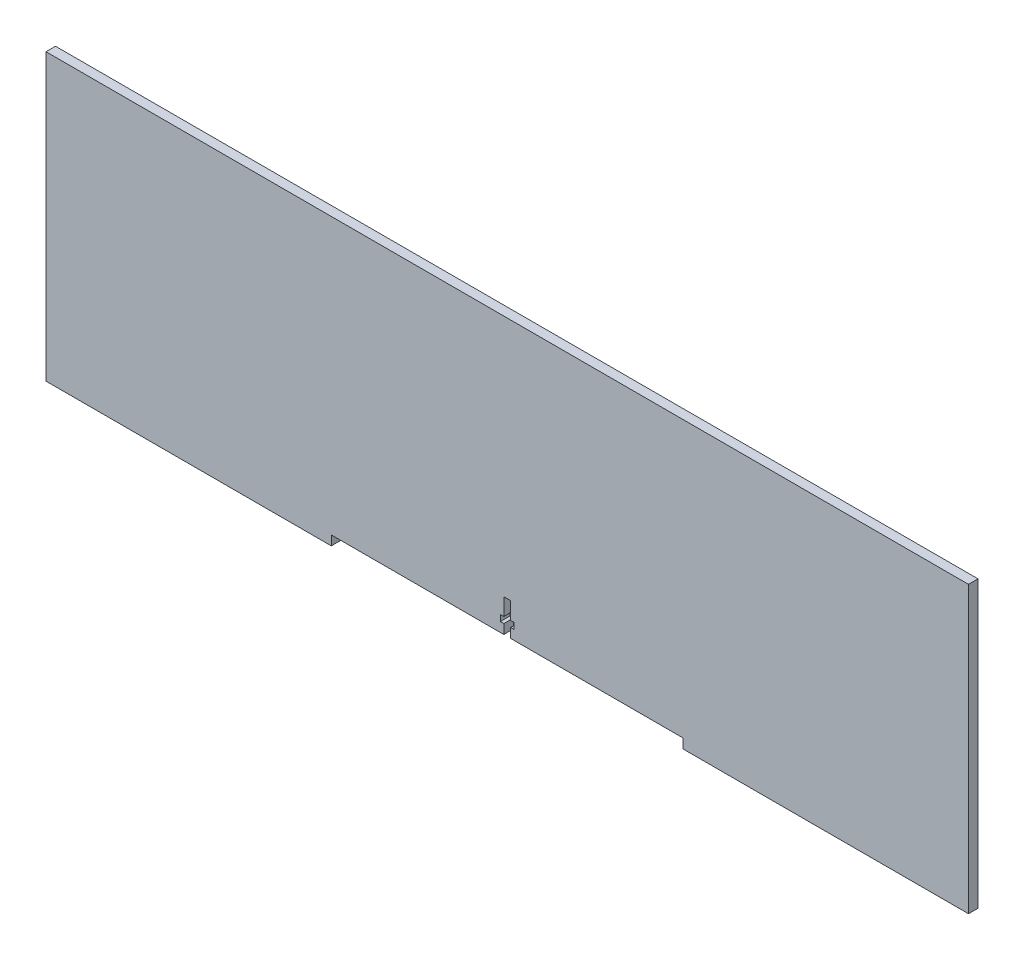
SolidWorks part; units mm, degrees
ref_plane "Alzado" through (0, 0, 0) normal (0, 0, 1) x (1, 0, 0)
ref_plane "Planta" through (0, 0, 0) normal (0, 1, 0) x (1, 0, 0)
ref_plane "Vista lateral" through (0, 0, 0) normal (1, 0, 0) x (0, 0, -1)
sketch "Croquis1" plane through (0, 0, 0) normal (0, 0, 1) x (1, 0, 0)
  line L0 (820, 0) -> (820, -363.7923) construction
  line L1 (0, 0) -> (185, 0)
  line L2 (0, 0) -> (0, 145)
  line L3 (0, 145) -> (1640, 145)
  line L4 (1640, 0) -> (1640, 145)
  line L5 (183.7346, 0) -> (185, 0)
  line L9 (485, -5) -> (185, -5)
  line L11 (670, 0) -> (670, -5)
  line L12 (670, -5) -> (970, -5)
  line L13 (970, 0) -> (970, -5)
  line L15 (1155, 0) -> (1155, -5)
  line L16 (1155, -5) -> (1455, -5)
  line L17 (1455, 0) -> (1455, -5)
  line L18 (185, 0) -> (185, -5)
  line L19 (485, 0) -> (481.1866, 0)
  line L20 (485, 0) -> (485, -5)
  line L21 (481.1866, 0) -> (670, 0)
  line L22 (970, 0) -> (1155, 0)
  line L23 (1455, 0) -> (1640, 0)
  point P15 (820, -5)
  dimension "D1" = 1640
  dimension "D2" = 145
  dimension "D3" = 5
  dimension "D4" = 185
  dimension "D5" = 300
  dimension "D6" = 300
  dimension "D7" = 5
  dimension "D8" = 185
extrude "Saliente-Extruir1" add sketch "Croquis1" along normal blind 5
sketch "Croquis2" plane through (0, 0, 5) normal (0, 0, 1) x (1, 0, 0)
  line L0 (1640, 72.5) -> (1561.7814, 72.5) construction
  line L1 (1640, 0) -> (1640, 145) construction
  line L2 (0, 145) -> (1640, 145) construction
  line L3 (1640, 126.25) -> (1635, 126.25)
  line L4 (1640, 126.25) -> (1640, 91.25)
  line L5 (1640, 91.25) -> (1635, 91.25)
  line L6 (1635, 126.25) -> (1635, 91.25)
  line L7 (1640, 53.75) -> (1635, 53.75)
  line L8 (1635, 18.75) -> (1635, 53.75)
  line L9 (1640, 18.75) -> (1635, 18.75)
  line L10 (1640, 18.75) -> (1640, 53.75)
  line L11 (820, 145) -> (820, 72.5) construction
  line L12 (0, 18.75) -> (0, 53.75)
  line L13 (0, 18.75) -> (5, 18.75)
  line L14 (5, 18.75) -> (5, 53.75)
  line L15 (0, 53.75) -> (5, 53.75)
  line L16 (0, 91.25) -> (5, 91.25)
  line L17 (5, 126.25) -> (5, 91.25)
  line L18 (0, 126.25) -> (5, 126.25)
  line L19 (0, 126.25) -> (0, 91.25)
  dimension "D1" = 35
  dimension "D2" = 18.75
  dimension "D3" = 5
extrude "Cortar-Extruir1" cut sketch "Croquis2" against normal blind 5 contours L7 L8 L9 L10 | L4 L3 L6 L5 | L16 L17 L18 L19 | L12 L15 L14 L13
sketch "Croquis3" plane through (0, 0, 5) normal (0, 0, 1) x (1, 0, 0)
  line L0 (577.5, 0) -> (577.5, 72.6456) construction
  line L1 (485, 0) -> (670, 0) construction
  line L2 (820, -5) -> (820, 72.6456) construction
  line L3 (670, -5) -> (970, -5) construction
  line L4 (579.3, 0) -> (575.7, 0)
  line L5 (575.7, 0) -> (575.7, 5)
  line L6 (575.7, 5) -> (573.9, 5)
  line L7 (573.9, 5) -> (573.9, 8.2)
  line L8 (573.9, 8.2) -> (575.7, 8.2)
  line L9 (575.7, 8.2) -> (575.7, 17.2)
  line L10 (575.7, 17.2) -> (579.3, 17.2)
  line L11 (579.3, 8.2) -> (579.3, 17.2)
  line L12 (581.1, 8.2) -> (579.3, 8.2)
  line L13 (581.1, 5) -> (581.1, 8.2)
  line L14 (579.3, 5) -> (581.1, 5)
  line L15 (579.3, 0) -> (579.3, 5)
  line L16 (1064.3, 8.2) -> (1064.3, 17.2)
  line L17 (1066.1, 8.2) -> (1064.3, 8.2)
  line L18 (1066.1, 5) -> (1066.1, 8.2)
  line L19 (1064.3, 5) -> (1066.1, 5)
  line L20 (1064.3, 0) -> (1064.3, 5)
  line L21 (1060.7, 0) -> (1064.3, 0)
  line L22 (1060.7, 0) -> (1060.7, 5)
  line L23 (1060.7, 5) -> (1058.9, 5)
  line L24 (1058.9, 5) -> (1058.9, 8.2)
  line L25 (1058.9, 8.2) -> (1060.7, 8.2)
  line L26 (1060.7, 8.2) -> (1060.7, 17.2)
  line L27 (1064.3, 17.2) -> (1060.7, 17.2)
  point P16 (577.5, 17.2)
  dimension "D1" = 1.8
  dimension "D2" = 5
  dimension "D3" = 1.8
  dimension "D4" = 3.2
  dimension "D5" = 1.8
  dimension "D6" = 9
extrude "Cortar-Extruir2" cut sketch "Croquis3" against normal blind 10 contours L10 L11 L12 L13 L14 L15 L4 L5 L6 L7 L8 L9 | L16 L27 L26 L25 L24 L23 L22 L21 L20 L19 L18 L17
sketch "Croquis4" plane through (0, 0, 5) normal (0, 0, 1) x (1, 0, 0)
  line L0 (335, -5) -> (335, 145)
  line L1 (485, -5) -> (185, -5) construction
  line L2 (0, 145) -> (1640, 145) construction
  line L3 (335, 145) -> (820, 145)
  line L4 (820, 145) -> (820, -5)
  line L5 (670, -5) -> (970, -5) construction
  line L6 (820, -5) -> (335, -5)
  line L7 (820, 145) -> (1680.9053, 145)
  line L8 (1680.9053, 145) -> (1680.9053, -135.2151)
  line L9 (1680.9053, -135.2151) -> (820, -135.2151)
  line L10 (820, -135.2151) -> (820, -5)
  line L11 (335, -5) -> (335, -117.5316)
  line L12 (335, -117.5316) -> (-54.1262, -117.5316)
  line L13 (-54.1262, -117.5316) -> (-54.1262, 245.6272)
  line L14 (-54.1262, 245.6272) -> (335, 145)
extrude "Cortar-Extruir3" cut sketch "Croquis4" against normal blind 10 contours L10 L9 L8 L7 L4 | L14 L13 L12 L11 L0
